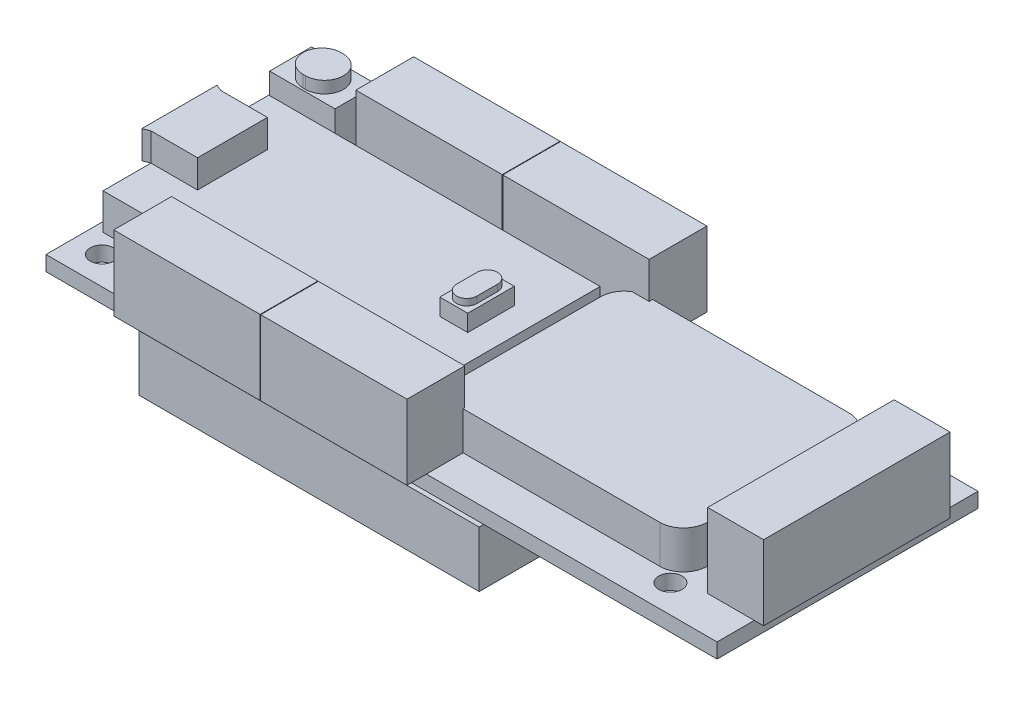
SolidWorks part; units mm, degrees
ref_plane "Front Plane" through (0, 0, 0) normal (0, 0, 1) x (1, 0, 0)
ref_plane "Top Plane" through (0, 0, 0) normal (0, 1, 0) x (1, 0, 0)
ref_plane "Right Plane" through (0, 0, 0) normal (1, 0, 0) x (0, 0, -1)
sketch "Sketch1" plane through (0, 0, 0) normal (0, 1, 0) x (1, 0, 0)
  line L0 (0, 0) -> (-36, 0) construction
  line L1 (36, -14) -> (-36, -14)
  line L2 (36, -14) -> (36, 14)
  line L3 (36, 14) -> (-36, 14)
  line L4 (-36, -14) -> (-36, 14)
  line L5 (36, -14) -> (-36, 14) construction
  line L6 (36, 14) -> (-36, -14) construction
  circle A0 centre (-33, -11) radius 1.25
  circle A1 centre (28, -11) radius 1.25
  circle A3 centre (-30.96, 1.27) radius 0.5
  circle A5 centre (28, 11) radius 1.25
  circle A6 centre (-30.96, -1.27) radius 0.5
  point P0 (0, 0)
  dimension "D3" = 2.5
  dimension "D8" = 1.27
  dimension "D9" = 1
  dimension "D11" = 5.04
  dimension "D1" = 28
  dimension "D2" = 72
  dimension "D4" = 3
  dimension "D5" = 3
  dimension "D7" = 64
extrude "Boss-Extrude1" add sketch "Sketch1" along normal blind 1.6
sketch "Sketch2" plane through (0, 1.6, 0) normal (0, 1, 0) x (1, 0, 0)
  line L0 (-36, 14) -> (-36, -14) construction
  line L1 (-35, 8.9) -> (0.56, 8.9)
  line L2 (-35, 8.9) -> (-35, -8.88)
  line L3 (-35, -8.88) -> (0.56, -8.88)
  line L4 (0.56, 8.9) -> (0.56, -8.88)
  line L5 (36, 14) -> (-36, 14) construction
  dimension "D1" = 1
  dimension "D2" = 5.1
  dimension "D3" = 17.78
  dimension "D4" = 35.56
extrude "Boss-Extrude2" add sketch "Sketch2" along normal blind 3.86
sketch "Sketch3" plane through (0, 5.46, 0) normal (0, 1, 0) x (1, 0, 0)
  line L0 (-35, 8.9) -> (-35, -8.88) construction
  line L1 (-35, 3.76) -> (-30, 3.76)
  line L3 (-35, -3.74) -> (-30, -3.74)
  line L4 (-30, 3.76) -> (-30, -3.74)
  line L5 (0.56, -8.88) -> (0.56, 8.9) construction
  line L6 (-35.7, 4.04) -> (-35.7, -4.02)
  line L7 (-35.7, 4.04) -> (-35, 3.76)
  line L8 (-35.7, -4.02) -> (-35, -3.74)
  point P6 (-30, 0.01)
  point P9 (0.56, 0.01)
  point P12 (-35.7, 0.01)
  dimension "D1" = 7.5
  dimension "D2" = 5
  dimension "D4" = 8.06
extrude "Boss-Extrude3" add sketch "Sketch3" along normal blind 3
sketch "Sketch4" plane through (0, 5.46, 0) normal (0, 1, 0) x (1, 0, 0)
  line L0 (0.56, -8.88) -> (0.56, 8.9) construction
  line L1 (-5.26, 2.51) -> (-2.26, 2.51)
  line L2 (-5.26, 2.51) -> (-5.26, -2.49)
  line L3 (-5.26, -2.49) -> (-2.26, -2.49)
  line L4 (-2.26, 2.51) -> (-2.26, -2.49)
  line L5 (-5.26, 2.51) -> (-2.26, -2.49) construction
  line L6 (-5.26, -2.49) -> (-2.26, 2.51) construction
  line L7 (-35, 8.9) -> (-35, 3.76) construction
  point P0 (-3.76, 0.01)
  point P5 (0, 0)
  point P8 (0.56, 0.01)
  dimension "D1" = 3
  dimension "D2" = 5
  dimension "D3" = 31.24
extrude "Boss-Extrude4" add sketch "Sketch4" along normal blind 1.8
sketch "Sketch5" plane through (0, 7.26, 0) normal (0, 1, 0) x (1, 0, 0)
  line L0 (-3.76, 1.11) -> (-3.76, -1.09) construction
  line L1 (-2.66, 1.11) -> (-2.66, -1.09)
  line L2 (-4.86, 1.11) -> (-4.86, -1.09)
  line L3 (-5.26, 2.51) -> (-5.26, -2.49) construction
  line L4 (-2.26, 2.51) -> (-5.26, 2.51) construction
  arc A0 (-2.66, 1.11) -> (-4.86, 1.11) centre (-3.76, 1.11) ccw
  arc A1 (-4.86, -1.09) -> (-2.66, -1.09) centre (-3.76, -1.09) ccw
  point P2 (-3.76, 0.01)
  point P7 (0, 0)
  point P10 (-5.26, 0.01)
  point P13 (-3.76, 2.51)
  dimension "D1" = 2.2
  dimension "D2" = 2.2
extrude "Boss-Extrude5" add sketch "Sketch5" along normal blind 0.7
sketch "Sketch6" plane through (0, 1.6, 0) normal (0, 1, 0) x (1, 0, 0)
  line L0 (-36, 14) -> (-36, -14) construction
  line L1 (4.315, 10.27) -> (25.905, 10.27)
  line L2 (1.775, 7.73) -> (1.775, -7.51)
  line L3 (4.315, -10.05) -> (25.905, -10.05)
  line L4 (28.445, 7.73) -> (28.445, -7.51)
  line L5 (1.775, 10.27) -> (28.445, -10.05) construction
  line L6 (1.775, -10.05) -> (28.445, 10.27) construction
  line L8 (36, 14) -> (-36, 14) construction
  arc A0 (28.445, -7.51) -> (25.905, -10.05) centre (25.905, -7.51) cw
  arc A1 (4.315, -10.05) -> (1.775, -7.51) centre (4.315, -7.51) cw
  arc A2 (1.775, 7.73) -> (4.315, 10.27) centre (4.315, 7.73) cw
  arc A3 (28.445, 7.73) -> (25.905, 10.27) centre (25.905, 7.73) ccw
  point P0 (15.11, 0.11)
  point P7 (15.01, 1.0446)
  dimension "D5" = 2.54
  dimension "D1" = 51.11
  dimension "D2" = 3.73
  dimension "D3" = 20.32
  dimension "D4" = 26.67
extrude "Boss-Extrude6" add sketch "Sketch6" along normal blind 4.09
sketch "Sketch7" plane through (0, 1.6, 0) normal (0, 1, 0) x (1, 0, 0)
  line L0 (36, 14) -> (-36, 14) construction
  line L1 (-26.65, 16.1) -> (-10.95, 16.1)
  line L2 (-26.65, 16.1) -> (-26.65, 9.9)
  line L3 (-26.65, 9.9) -> (-10.95, 9.9)
  line L4 (-10.95, 16.1) -> (-10.95, 9.9)
  line L5 (-26.65, 16.1) -> (-10.95, 9.9) construction
  line L6 (-26.65, 9.9) -> (-10.95, 16.1) construction
  line L7 (-36, 14) -> (-36, -14) construction
  line L8 (0.56, 0.01) -> (-36.5415, 0.01) construction
  line L9 (-10.89, 16.1) -> (4.81, 16.1)
  line L10 (-10.89, 16.1) -> (-10.89, 9.9)
  line L11 (-10.89, 9.9) -> (4.81, 9.9)
  line L12 (4.81, 16.1) -> (4.81, 9.9)
  line L13 (-10.89, 16.1) -> (4.81, 9.9) construction
  line L14 (-10.89, 9.9) -> (4.81, 16.1) construction
  line L15 (0.56, -8.88) -> (0.56, 8.9) construction
  line L16 (-10.89, -9.88) -> (4.81, -16.08) construction
  line L17 (-10.89, -16.08) -> (4.81, -9.88) construction
  line L18 (-26.65, -9.88) -> (-10.95, -16.08) construction
  line L19 (-26.65, -16.08) -> (-10.95, -9.88) construction
  line L20 (4.81, -16.08) -> (4.81, -9.88)
  line L21 (-10.89, -9.88) -> (4.81, -9.88)
  line L22 (-10.89, -16.08) -> (-10.89, -9.88)
  line L23 (-10.89, -16.08) -> (4.81, -16.08)
  line L24 (-10.95, -16.08) -> (-10.95, -9.88)
  line L25 (-26.65, -9.88) -> (-10.95, -9.88)
  line L26 (-26.65, -16.08) -> (-26.65, -9.88)
  line L27 (-26.65, -16.08) -> (-10.95, -16.08)
  point P0 (-18.8, 13)
  point P12 (-3.04, 13)
  point P26 (-3.04, -12.98)
  point P27 (-18.8, -12.98)
  dimension "D1" = 6.2
  dimension "D2" = 15.7
  dimension "D3" = 1
  dimension "D4" = 9.35
  dimension "D5" = 25.11
  dimension "D6" = 15.7
extrude "Boss-Extrude7" add sketch "Sketch7" along normal blind 8
sketch "Sketch8" plane through (0, 0, 0) normal (0, -1, 0) x (-1, 0, 0)
  line L0 (36, 14) -> (36, -14) construction
  line L1 (-2.55, -6.2703) -> (-32.55, -6.2703)
  line L2 (-2.55, -6.2703) -> (-2.55, 6.7297)
  line L3 (-2.55, 6.7297) -> (-32.55, 6.7297)
  line L4 (-32.55, -6.2703) -> (-32.55, 6.7297)
  line L5 (-2.55, -6.2703) -> (-32.55, 6.7297) construction
  line L6 (-2.55, 6.7297) -> (-32.55, -6.2703) construction
  point P0 (-17.55, 0.2297)
  dimension "D1" = 30
  dimension "D2" = 13
  dimension "D3" = 53.55
extrude "Boss-Extrude8" add sketch "Sketch8" along normal blind 1.5
sketch "Sketch9" plane through (0, 1.6, 0) normal (0, 1, 0) x (1, 0, 0)
  line L0 (-36, 14) -> (-36, -14) construction
  line L1 (31, 10.0036) -> (37, 10.0036)
  line L2 (31, 10.0036) -> (31, -10.0036)
  line L3 (31, -10.0036) -> (37, -10.0036)
  line L4 (37, 10.0036) -> (37, -10.0036)
  line L5 (31, 10.0036) -> (37, -10.0036) construction
  line L6 (31, -10.0036) -> (37, 10.0036) construction
  point P0 (34, 0)
  point P7 (0, 0)
  dimension "D1" = 6
  dimension "D2" = 20.0073
  dimension "D3" = 70
extrude "Boss-Extrude9" add sketch "Sketch9" along normal blind 8
sketch "Sketch10" plane through (0, 0, 0) normal (0, -1, 0) x (-1, 0, 0)
  line L1 (25.5317, -14.49) -> (-10.9683, -14.49)
  line L2 (25.5317, -14.49) -> (25.5317, 14.51)
  line L3 (25.5317, 14.51) -> (-10.9683, 14.51)
  line L4 (-10.9683, -14.49) -> (-10.9683, 14.51)
  line L5 (25.5317, -14.49) -> (-10.9683, 14.51) construction
  line L6 (25.5317, 14.51) -> (-10.9683, -14.49) construction
  point P0 (7.2817, 0.01)
  point P5 (12.5215, 0)
  point P6 (8.4349, 0)
  point P7 (7.2817, 0.01)
  dimension "D1" = 29
  dimension "D2" = 36.5
extrude "Boss-Extrude10" add sketch "Sketch10" along normal blind 6
sketch "Sketch12" plane through (0, 1.6, 0) normal (0, 1, 0) x (1, 0, 0)
  line L0 (-36, 14) -> (-36, -14) construction
  line L5 (-28.245, 9.25) -> (-35.255, 9.25)
  line L6 (-28.245, 9.25) -> (-28.245, 13.75)
  line L7 (-28.245, 13.75) -> (-35.255, 13.75)
  line L8 (-35.255, 9.25) -> (-35.255, 13.75)
  line L9 (-28.245, 9.25) -> (-35.255, 13.75) construction
  line L10 (-28.245, 13.75) -> (-35.255, 9.25) construction
  line L11 (-26.65, 14) -> (-36, 14) construction
  point P0 (-31.75, 11.5)
  dimension "D1" = 4.5
  dimension "D2" = 7.01
  dimension "D3" = 4.25
  dimension "D4" = 2.5
extrude "Boss-Extrude11" add sketch "Sketch12" along normal blind 5.79
sketch "Sketch13" plane through (0, 7.39, 0) normal (0, 1, 0) x (1, 0, 0)
  line L0 (-31.88, 11.5) -> (-31.62, 11.5) construction
  line L1 (-31.88, 13.53) -> (-31.62, 13.53)
  line L2 (-31.88, 9.47) -> (-31.62, 9.47)
  line L3 (-28.245, 9.25) -> (-28.245, 13.75) construction
  line L4 (-28.245, 13.75) -> (-35.255, 13.75) construction
  line L5 (-33.91, 9.25) -> (-33.91, 13.75) construction
  line L6 (-35.255, 9.25) -> (-28.245, 9.25) construction
  line L7 (-29.59, 9.25) -> (-29.59, 13.75) construction
  line L8 (-31.75, 13.75) -> (-31.75, 9.25) construction
  arc A0 (-31.88, 13.53) -> (-31.88, 9.47) centre (-31.88, 11.5) ccw
  arc A1 (-31.62, 9.47) -> (-31.62, 13.53) centre (-31.62, 11.5) ccw
  point P2 (-31.75, 11.5)
  point P10 (-28.245, 11.5)
  point P13 (-31.75, 13.75)
  point P21 (0, 0)
  dimension "D2" = 4.32
  dimension "D1" = 4.06
extrude "Boss-Extrude12" add sketch "Sketch13" along normal blind 1.27
